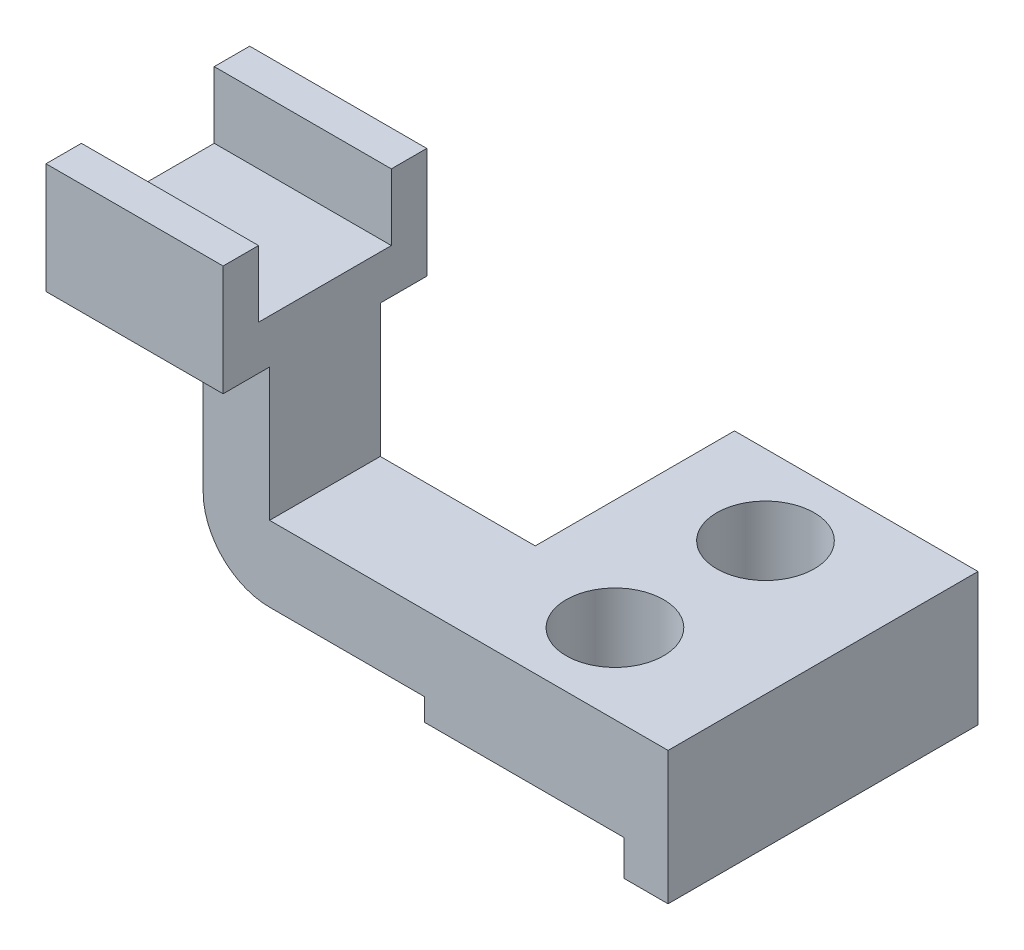
SolidWorks part; units mm, degrees
ref_plane "Front Plane" through (0, 0, 0) normal (0, 0, 1) x (1, 0, 0)
ref_plane "Top Plane" through (0, 0, 0) normal (0, 1, 0) x (1, 0, 0)
ref_plane "Right Plane" through (0, 0, 0) normal (1, 0, 0) x (0, 0, -1)
sketch "Sketch1" plane through (0, 0, 0) normal (0, 0, 1) x (1, 0, 0)
  line L3 (39.1102, -2.0385) -> (39.1102, 14.6989)
  line L4 (39.1102, 14.6989) -> (-50.8898, 14.6989)
  line L5 (-50.8898, 14.6989) -> (-50.8898, -2.3011)
  line L6 (-50.8898, -2.3011) -> (-15.8898, -2.3011)
  line L8 (-65.8898, 12.6989) -> (-65.8898, 44.6989)
  line L9 (-65.8898, 44.6989) -> (-50.8898, 44.6989)
  line L10 (-50.8898, 44.6989) -> (-50.8898, 14.6989)
  line L11 (-15.8898, -2.3011) -> (-15.8898, -7.3156)
  line L12 (-15.8898, -7.3156) -> (29.1102, -7.3156)
  line L13 (29.1102, -7.3156) -> (29.1102, -15.3156)
  line L14 (29.1102, -15.3156) -> (39.1102, -15.3156)
  line L15 (39.1102, -15.3156) -> (39.1102, -2.0385)
  arc A0 (-65.8898, 12.6989) -> (-50.8898, -2.3011) centre (-50.8898, 12.6989) ccw
  dimension "D5" = 15
  dimension "D1" = 15
  dimension "D2" = 8
  dimension "D3" = 45
  dimension "D4" = 55
  dimension "D6" = 17
  dimension "D7" = 105
  dimension "D8" = 30
extrude "Boss-Extrude2" add sketch "Sketch1" against normal blind 25 contours L14 L15 L3 L4 L5 L6 L11 L12 L13 | L8 A0 L5 L10 L9
sketch "Sketch2" plane through (0, 0, -25) normal (0, 0, -1) x (-1, 0, 0)
  line L0 (-39.1102, -15.3156) -> (-39.1102, 14.6989)
  line L1 (-39.1102, -15.3156) -> (-29.1102, -15.3156)
  line L2 (-29.1102, -15.3156) -> (-29.1102, -7.3156)
  line L3 (-29.1102, -7.3156) -> (15.8898, -7.3156)
  line L4 (15.8898, -2.3011) -> (15.8898, 14.6989)
  line L5 (-39.1102, 14.6989) -> (50.8898, 14.6989) construction
  line L6 (15.8898, 14.6989) -> (-39.1102, 14.6989)
  line L7 (15.8898, -2.3011) -> (15.8898, -7.3156)
extrude "Boss-Extrude3" add sketch "Sketch2" along normal blind 45
sketch "Sketch3" plane through (0, 44.6989, 0) normal (0, 1, 0) x (1, 0, 0)
  line L1 (-50.8898, 35.5) -> (-90.8898, 35.5)
  line L2 (-90.8898, 35.5) -> (-90.8898, -10.5)
  line L3 (-90.8898, -10.5) -> (-50.8898, -10.5)
  line L6 (-50.8898, -10.5) -> (-50.8898, 35.5)
  line L7 (-65.8898, 0) -> (-65.8898, 25)
  point P0 (-65.8898, 12.5)
  point P4 (-50.8898, 12.5)
  line M8 (-65.8898, 0) -> (-50.8898, 0)
  line M9 (-50.8898, 0) -> (-50.8898, 25)
  line M10 (-50.8898, 25) -> (-65.8898, 25)
  line M11 (-65.8898, 25) -> (-65.8898, 0)
  dimension "D1" = 40
  dimension "D2" = 46
extrude "Boss-Extrude4" add sketch "Sketch3" along normal blind 25 contours L3 L6 L1 L2 M8 M11 M10 | M11 M8 M9 M10
sketch "Sketch4" plane through (0, 69.6989, 0) normal (0, 1, 0) x (1, 0, 0)
  line L0 (-90.8898, -2.5) -> (-50.8898, -2.5)
  line L1 (-90.8898, 35.5) -> (-90.8898, -10.5) construction
  line L2 (-50.8898, -10.5) -> (-50.8898, 35.5) construction
  line L3 (-50.8898, -2.5) -> (-50.8898, 27.5)
  line L4 (-50.8898, 27.5) -> (-90.8898, 27.5)
  line L5 (-90.8898, 27.5) -> (-90.8898, -2.5)
  line L6 (-90.8898, 27.5) -> (-90.8898, 35.5)
  line L7 (-90.8898, -2.5) -> (-90.8898, -10.5)
  line M3 (-50.8898, -10.5) -> (-50.8898, 35.5)
  line M5 (-90.8898, 35.5) -> (-90.8898, -10.5)
  dimension "D1" = 8
  dimension "D2" = 8
extrude "Cut-Extrude1" cut sketch "Sketch4" against normal blind 15 contours L4 L0 M3 M5
sketch "Sketch5" plane through (0, 14.6989, 0) normal (0, 1, 0) x (1, 0, 0)
  line L0 (39.1102, 0) -> (-50.8898, 0) construction
  line L1 (39.1102, 70) -> (39.1102, 0) construction
  line L2 (-15.8898, 70) -> (-15.8898, 25) construction
  circle A0 centre (9.1102, 18) radius 11
  circle A1 centre (9.1102, 52) radius 11
  dimension "D1" = 18
  dimension "D2" = 34
  dimension "D3" = 30
  dimension "D4" = 30
  dimension "D5" = 55
extrude "Cut-Extrude2" cut sketch "Sketch5" against normal through all
